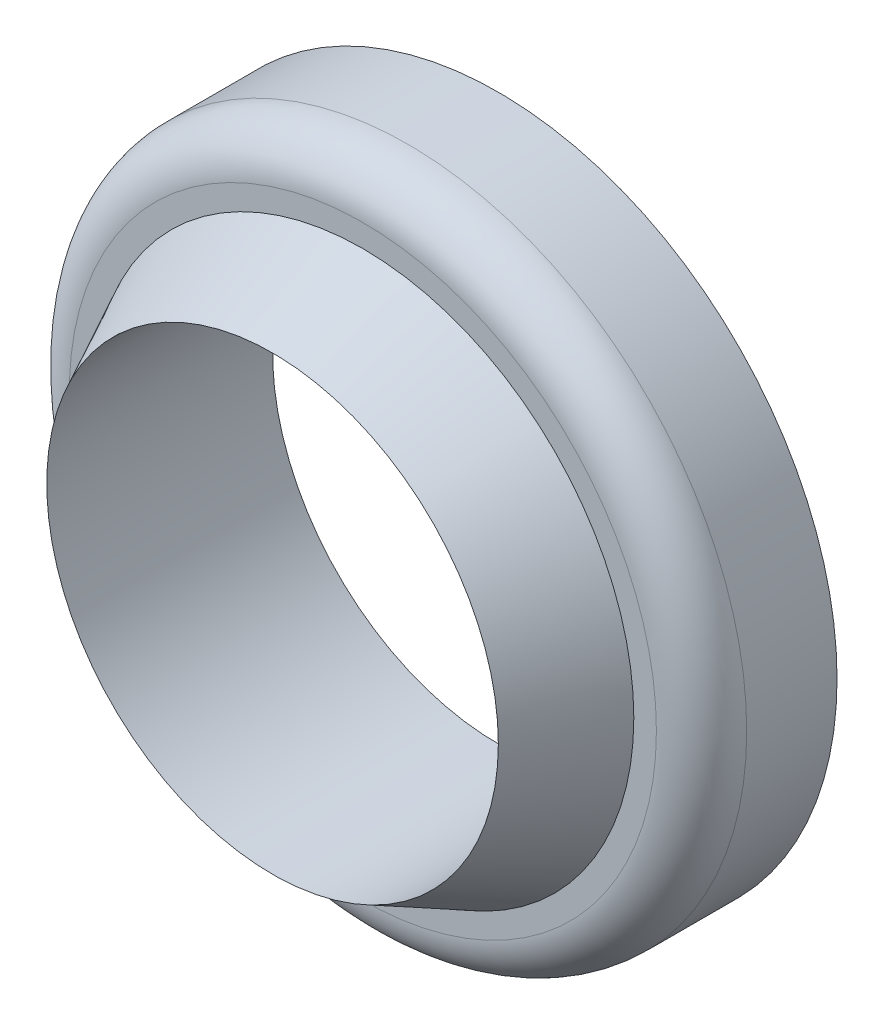
SolidWorks part; units mm, degrees
ref_plane "Piano frontale" through (0, 0, 0) normal (0, 0, 1) x (1, 0, 0)
ref_plane "Piano superiore" through (0, 0, 0) normal (0, 1, 0) x (1, 0, 0)
ref_plane "Piano destro" through (0, 0, 0) normal (1, 0, 0) x (0, 0, -1)
sketch "Schizzo1" plane through (0, 0, 0) normal (1, 0, 0) x (0, 0, -1)
  line L0 (-48.0552, 0) -> (55.2722, 0) construction
  line L1 (0, 5) -> (0, 7.5)
  line L2 (0, 7.5) -> (-2, 7.5)
  line L3 (-3, 6.5) -> (-3, 6)
  line L4 (-3, 6) -> (-5, 5)
  line L6 (-5, 5) -> (0, 5)
  line L7 (55, 0) -> (-55, 0) construction
  arc A0 (-3, 6.5) -> (-2, 7.5) centre (-2, 6.5) cw
  point P11 (-3, 7.5)
  dimension "D6" = 1
  dimension "D1" = 10
  dimension "D2" = 15
  dimension "D3" = 2
  dimension "D4" = 3
  dimension "D5" = 2.2361
revolve "Rivoluzione1" add sketch "Schizzo1" angle 360 about L0
